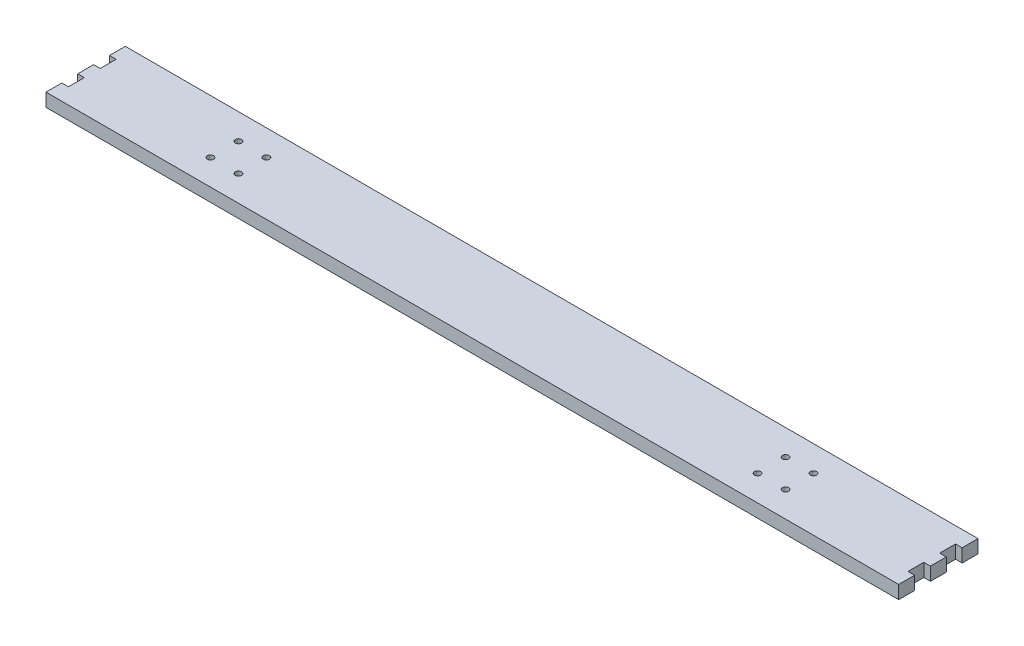
SolidWorks part; units mm, degrees
ref_plane "Front Plane" through (0, 0, 0) normal (0, 0, 1) x (1, 0, 0)
ref_plane "Top Plane" through (0, 0, 0) normal (0, 1, 0) x (1, 0, 0)
ref_plane "Right Plane" through (0, 0, 0) normal (1, 0, 0) x (0, 0, -1)
sketch "Sketch1" plane through (0, 0, 0) normal (0, 1, 0) x (1, 0, 0)
  line L1 (-204.7875, -19.05) -> (204.7875, -19.05)
  line L2 (-204.7875, -19.05) -> (-204.7875, 19.05)
  line L3 (-204.7875, 19.05) -> (204.7875, 19.05)
  line L4 (204.7875, -19.05) -> (204.7875, 19.05)
  line L5 (-204.7875, -19.05) -> (204.7875, 19.05) construction
  line L6 (-204.7875, 19.05) -> (204.7875, -19.05) construction
  point P0 (0, 0)
  dimension "D1" = 409.575
  dimension "D2" = 38.1
extrude "Boss-Extrude1" add sketch "Sketch1" along normal blind 6.35
sketch "Sketch2" plane through (0, 6.35, 0) normal (0, 1, 0) x (1, 0, 0)
  line L0 (-204.7875, 19.05) -> (-204.7875, -19.05) construction
  line L1 (-204.7875, 11.43) -> (-201.6125, 11.43)
  line L2 (-204.7875, 11.43) -> (-204.7875, 3.81)
  line L3 (-204.7875, 3.81) -> (-201.6125, 3.81)
  line L4 (-201.6125, 11.43) -> (-201.6125, 3.81)
  line L5 (204.7875, 19.05) -> (-204.7875, 19.05) construction
  line L6 (-204.7875, -3.81) -> (-204.7875, -11.43)
  line L7 (-204.7875, -3.81) -> (-201.6125, -3.81)
  line L8 (-201.6125, -3.81) -> (-201.6125, -11.43)
  line L9 (-204.7875, -11.43) -> (-201.6125, -11.43)
  dimension "D1" = 7.62
  dimension "D2" = 7.62
  dimension "D3" = 3.175
  dimension "D5" = 7.62
  dimension "D4" = 2
extrude "Cut-Extrude1" cut sketch "Sketch2" against normal up to next
mirror "Mirror1" about plane through (0, 0, 0) normal (1, 0, 0) of "Cut-Extrude1"
sketch "Sketch3" plane through (0, 6.35, 0) normal (0, 1, 0) x (1, 0, 0)
  line L0 (-138.1125, 6.7175) -> (-124.6775, 6.7175) construction
  line L1 (-124.6775, 6.7175) -> (-124.6775, -6.7175) construction
  line L2 (-124.6775, -6.7175) -> (-138.1125, -6.7175) construction
  line L3 (-138.1125, -6.7175) -> (-138.1125, 6.7175) construction
  circle A0 centre (-138.1125, 6.7175) radius 1.5
  circle A1 centre (-138.1125, -6.7175) radius 1.5
  circle A2 centre (-124.6775, 6.7175) radius 1.5
  circle A4 centre (-124.6775, -6.7175) radius 1.5
  point P10 (-124.6775, 0)
  dimension "D3" = 3
  dimension "D4" = 138.1125
  dimension "D1" = 19
extrude "Cut-Extrude2" cut sketch "Sketch3" against normal up to next
mirror "Mirror2" about plane through (0, 0, 0) normal (1, 0, 0) of "Cut-Extrude2"
